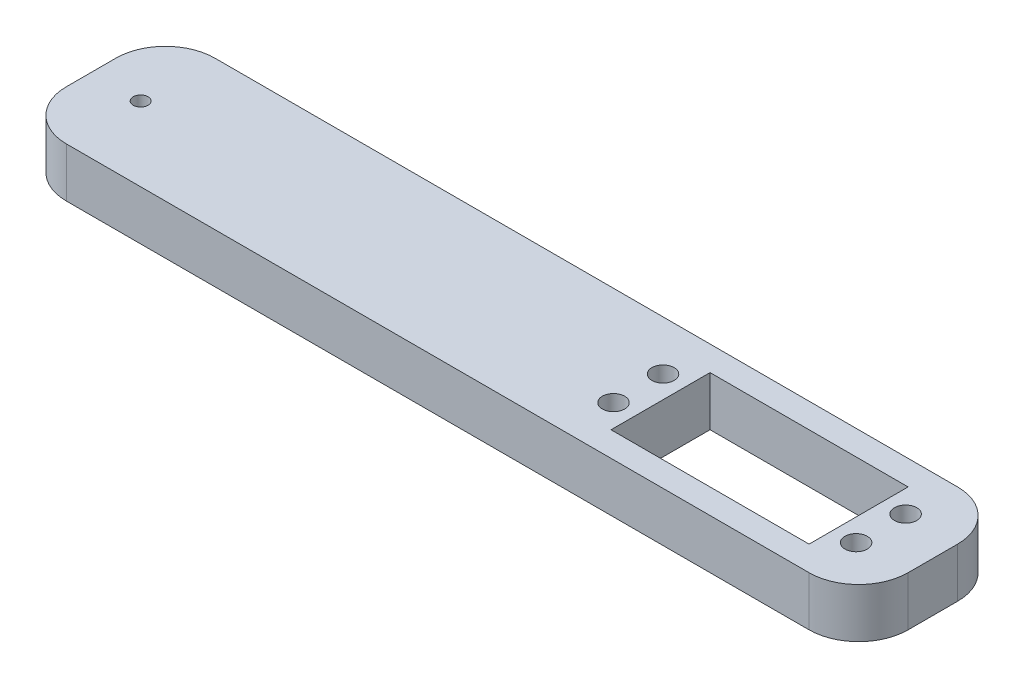
SolidWorks part; units mm, degrees
ref_plane "Alzado" through (0, 0, 0) normal (0, 0, 1) x (1, 0, 0)
ref_plane "Planta" through (0, 0, 0) normal (0, 1, 0) x (1, 0, 0)
ref_plane "Vista lateral" through (0, 0, 0) normal (1, 0, 0) x (0, 0, -1)
sketch "Croquis1" plane through (0, 0, 0) normal (0, 1, 0) x (1, 0, 0)
  line L1 (85, -15) -> (-85, -15)
  line L2 (85, -15) -> (85, 15)
  line L3 (85, 15) -> (-85, 15)
  line L4 (-85, -15) -> (-85, 15)
  line L5 (85, -15) -> (-85, 15) construction
  line L6 (85, 15) -> (-85, -15) construction
  line L8 (30, -10) -> (70, -10)
  line L9 (30, -10) -> (30, 10)
  line L10 (30, 10) -> (70, 10)
  line L11 (70, -10) -> (70, 10)
  point P0 (0, 0)
  point P12 (70, 0)
  dimension "D1" = 170
  dimension "D2" = 30
  dimension "D3" = 5
  dimension "D4" = 40
  dimension "D5" = 20
  dimension "D6" = 15
extrude "Saliente-Extruir1" add sketch "Croquis1" along normal blind 10
sketch "Croquis2" plane through (0, 10, 0) normal (0, 1, 0) x (1, 0, 0)
  line L0 (70, -10) -> (70, 10) construction
  line L3 (30, -10) -> (70, -10) construction
  line L4 (70, 0) -> (72.7854, 0) construction
  line L5 (50, 10) -> (50, -10) construction
  line L6 (70, 10) -> (30, 10) construction
  circle A0 centre (74.5, -5) radius 2.25
  circle A1 centre (74.5, 5) radius 2.25
  circle A2 centre (25.5, -5) radius 2.25
  circle A3 centre (25.5, 5) radius 2.25
  dimension "D3" = 4.5
  dimension "D1" = 4.5
  dimension "D2" = 5
extrude "Cortar-Extruir1" cut sketch "Croquis2" against normal blind 10
fillet "Redondeo3" radius 10 4 edges at (85, 5, 15) (-85, 5, 15) (-85, 5, -15) (85, 5, -15)
sketch "Croquis3" plane through (0, 10, 0) normal (0, 1, 0) x (1, 0, 0)
  line L2 (75, 15) -> (-75, 15) construction
  line L4 (-85, 5) -> (-85, -5) construction
  circle A0 centre (-75, 0) radius 1.5
  dimension "D1" = 3
  dimension "D2" = 15
  dimension "D3" = 10
extrude "Cortar-Extruir2" cut sketch "Croquis3" against normal blind 10
